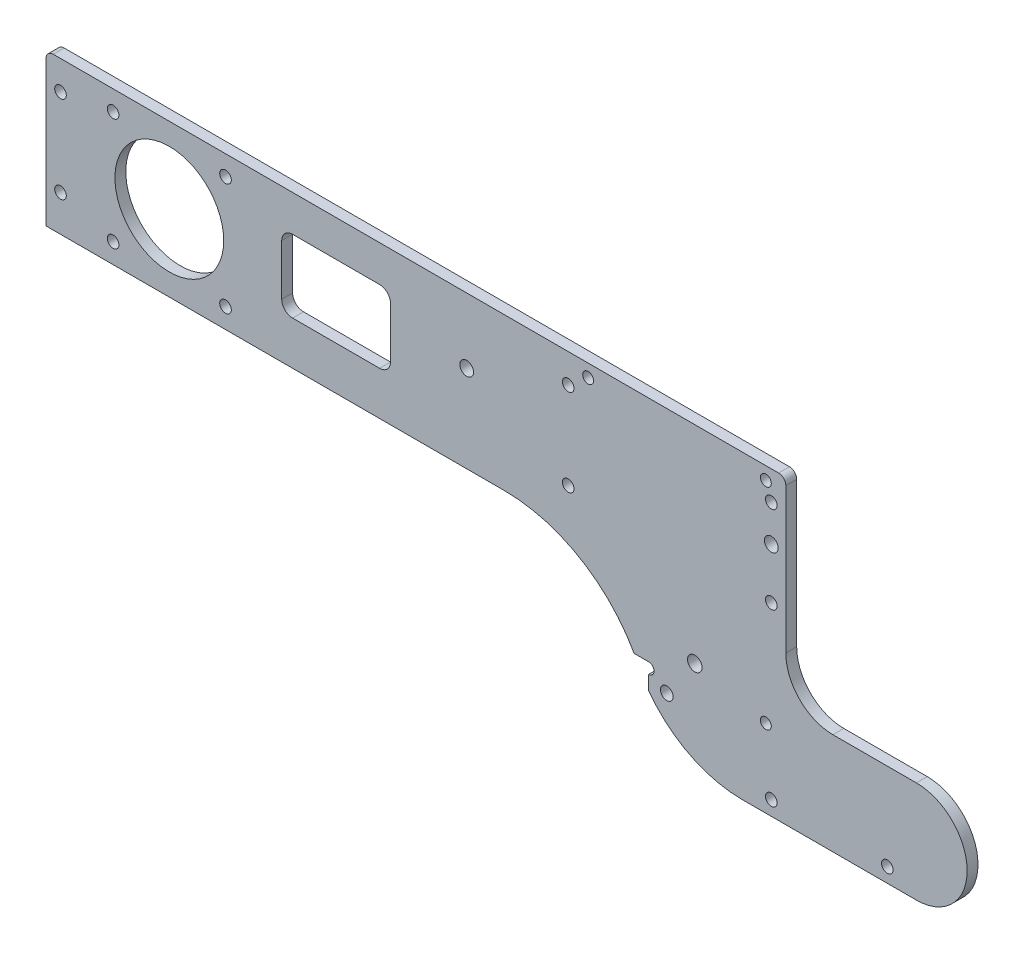
SolidWorks part; units mm, degrees
ref_plane "前视基准面" through (0, 0, 0) normal (0, 0, 1) x (1, 0, 0)
ref_plane "上视基准面" through (0, 0, 0) normal (0, 1, 0) x (1, 0, 0)
ref_plane "右视基准面" through (0, 0, 0) normal (1, 0, 0) x (0, 0, -1)
other "Configuration Table"
sketch "草图1" plane through (0, 0, 0) normal (0, 0, 1) x (1, 0, 0)
  line L1 (-34, 0) -> (-34, 40)
  line L3 (170, 40) -> (170, 0)
  line L4 (-15.5, 5.5) -> (15.5, 5.5) construction
  line L10 (-32, 42) -> (168, 42)
  line L15 (-34, 0) -> (92.3875, 0)
  line L17 (158, -41) -> (206, -41)
  line L20 (166, -37) -> (198, -37) construction
  line L21 (206, -13) -> (183, -13)
  circle A0 centre (15.5, 5.5) radius 1.6
  circle A1 centre (-15.5, 5.5) radius 1.6
  circle A2 centre (-15.5, 36.5) radius 1.6
  circle A3 centre (15.5, 36.5) radius 1.6
  circle A4 centre (166, 34) radius 1.6
  circle A5 centre (166, 10) radius 1.6
  circle A6 centre (-30, 10) radius 1.6
  circle A7 centre (-30, 34) radius 1.6
  arc A8 (168, 42) -> (170, 40) centre (168, 40) cw
  arc A9 (-34, 40) -> (-32, 42) centre (-32, 40) cw
  circle A10 centre (0, 21) radius 15
  arc A11 (92.3875, 0) -> (129.2384, -23.0274) centre (92.3875, -41) cw
  arc A13 (129.2384, -23.0274) -> (158, -41) centre (158, -9) ccw
  arc A14 (206, -41) -> (206, -13) centre (206, -27) ccw
  circle A16 centre (166, -37) radius 1.6
  circle A17 centre (198, -37) radius 1.6
  circle A24 centre (110, 34) radius 1.6
  circle A25 centre (110, 10) radius 1.6
  arc A27 (170, 0) -> (183, -13) centre (183, 0) ccw
  point P8 (0, 5.5)
  point P34 (-34, 42)
  point P48 (182, -41)
  point P49 (182, -37)
  dimension "D3" = 3.2
  dimension "D10" = 3.2
  dimension "D11" = 2
  dimension "D13" = 30
  dimension "D14" = 30
  dimension "D18" = 41
  dimension "D20" = 14
  dimension "D19" = 42
  dimension "D23" = 56
  dimension "D24" = 32
  dimension "D27" = 3.2
  dimension "D21" = 200
  dimension "D2" = 31
  dimension "D4" = 31
  dimension "D5" = 31
  dimension "D6" = 42
  dimension "D7" = 204
  dimension "D8" = 8
  dimension "D9" = 42
  dimension "D12" = 15.5
  dimension "D15" = 34
  dimension "D16" = 4
  dimension "D17" = 10
  dimension "D25" = 48
  dimension "D26" = 32
  dimension "D28" = 4
  dimension "D29" = 21
extrude "凸台-拉伸1" add sketch "草图1" along normal blind 3
sketch "草图3" plane through (0, 0, 3) normal (0, 0, 1) x (1, 0, 0)
  line L0 (158, -41) -> (206, -41) construction
  line L1 (128.1786, -21) -> (132.1786, -21)
  line L2 (128.1786, -21) -> (128.1786, -41)
  line L3 (128.1786, -41) -> (132.1786, -41)
  line L4 (132.1786, -21) -> (132.1786, -41)
  arc A1 (129.2384, -23.0274) -> (92.3875, 0) centre (92.3875, -41) ccw construction
  dimension "D1" = 20
  dimension "D2" = 4
extrude "切除-拉伸2" cut sketch "草图3" against normal blind 10
sketch "草图4" plane through (0, 0, 0) normal (0, 0, -1) x (-1, 0, 0)
  line L0 (-132.1786, -21) -> (-142.1786, -31)
  line L1 (-132.1786, -21) -> (-142.1786, -21)
  line L2 (-132.1786, -21) -> (-132.1786, -31)
  line L3 (-132.1786, -31) -> (-142.1786, -31)
  line L4 (-142.1786, -21) -> (-142.1786, -31)
  dimension "D1" = 10
  dimension "D2" = 10
sketch "草图5" plane through (0, 0, 0) normal (0, 0, -1) x (-1, 0, 0)
  line L0 (-132.1786, -21) -> (-142.1786, -31) construction
  point P0 (-137.1786, -26)
hole_wizard "孔1" positions "草图5" profile "草图6" legacy end condition through all
sketch "草图6" plane through (137.1786, -26, 0) normal (1, 0, 0) x (0, 1, 0)
  line L0 (0, 0) -> (0, 3)
  line L1 (0, 3) -> (1.75, 3)
  line L2 (1.75, 3) -> (1.75, 0)
  line L3 (1.75, 0) -> (0, 0)
  line L4 (0, 110) -> (0, -10) construction
  dimension "直径" = 3.5
  dimension "深度" = 3
sketch "草图10" plane through (0, 0, 0) normal (0, 0, -1) x (-1, 0, 0)
  line L1 (-168, 42) -> (-112, 42)
  line L2 (-168, 42) -> (-168, -43)
  line L3 (-168, -43) -> (-112, -43)
  line L4 (-112, 42) -> (-112, -43)
  line L5 (-164.5, 38.5) -> (-115.5, 38.5)
  line L6 (-164.5, 38.5) -> (-164.5, -19.5)
  line L7 (-164.5, -19.5) -> (-115.5, -19.5)
  line L8 (-115.5, 38.5) -> (-115.5, -19.5)
  dimension "D1" = 85
  dimension "D2" = 56
  dimension "D3" = 3.5
  dimension "D4" = 3.5
  dimension "D5" = 58
  dimension "D6" = 49
sketch "草图11" plane through (0, 0, 0) normal (0, 0, -1) x (-1, 0, 0)
  point P0 (-164.5, 38.5)
  point P3 (-115.5, 38.5)
  point P6 (-164.5, -19.5)
hole_wizard "孔3" positions "草图11" profile "草图12" legacy end condition through all
sketch "草图12" plane through (164.5, 38.5, 0) normal (1, 0, 0) x (0, 1, 0)
  line L0 (0, 0) -> (0, 3)
  line L1 (0, 3) -> (1.5, 3)
  line L2 (1.5, 3) -> (1.5, 0)
  line L3 (1.5, 0) -> (0, 0)
  line L4 (0, 110) -> (0, -10) construction
  dimension "直径" = 3
  dimension "深度" = 3
sketch "草图18" plane through (0, 0, 0) normal (0, 0, -1) x (-1, 0, 0)
  line L0 (-166, 34) -> (-166, 24)
  line L2 (-166, 24) -> (-82, 24)
  dimension "D1" = 10
  dimension "D2" = 84
sketch "草图19" plane through (0, 0, 0) normal (0, 0, -1) x (-1, 0, 0)
  point P0 (-166, 24)
  point P3 (-82, 24)
hole_wizard "孔6" positions "草图19" profile "草图20" legacy
sketch "草图20" plane through (166, 24, 0) normal (1, 0, 0) x (0, 1, 0)
  line L0 (0, 0) -> (0, 3)
  line L1 (0, 3) -> (1.9, 3)
  line L2 (1.9, 3) -> (1.9, 0)
  line L3 (1.9, 0) -> (0, 0)
  line L4 (0, 110) -> (0, -10) construction
  dimension "直径" = 3.8
  dimension "深度" = 3
sketch "草图23" plane through (0, 0, 0) normal (0, 0, -1) x (-1, 0, 0)
  point P0 (-144.906, -15.042)
hole_wizard "孔8" positions "草图23" profile "草图24" legacy
sketch "草图24" plane through (144.906, -15.042, 0) normal (1, 0, 0) x (0, 1, 0)
  line L0 (0, 0) -> (0, 3)
  line L1 (0, 3) -> (2, 3)
  line L2 (2, 3) -> (2, 0)
  line L3 (2, 0) -> (0, 0)
  line L4 (0, 110) -> (0, -10) construction
  dimension "直径" = 4
  dimension "深度" = 3
sketch "草图25" plane through (0, 0, 0) normal (0, 0, -1) x (-1, 0, 0)
  line L0 (-168, 42) -> (32, 42) construction
  line L1 (-31, 32) -> (-61, 32)
  line L2 (-31, 32) -> (-31, 12)
  line L3 (-31, 12) -> (-61, 12)
  line L4 (-61, 32) -> (-61, 12)
  line L5 (-31, 32) -> (-61, 12) construction
  line L6 (-31, 12) -> (-61, 32) construction
  line L7 (34, 40) -> (34, 0) construction
  point P0 (-46, 22)
  dimension "D1" = 20
  dimension "D2" = 80
  dimension "D3" = 30
  dimension "D4" = 20
extrude "切除-拉伸3" cut sketch "草图25" against normal blind 10
fillet "圆角1" radius 3 4 edges at (61, 12, 1.5) (31, 12, 1.5) (31, 32, 1.5) (61, 32, 1.5)
sketch "草图26" plane through (0, 0, 0) normal (0, 0, -1) x (-1, 0, 0)
  line L0 (-132.1786, -21) -> (-132.1786, -31) construction
  point P0 (-132.1786, -22.5)
  dimension "D1" = 1.5
hole_wizard "孔9" positions "草图26" profile "草图27" legacy end condition up to next
sketch "草图27" plane through (132.1786, -22.5, 0) normal (1, 0, 0) x (0, 1, 0)
  line L0 (0, 0) -> (0, 3)
  line L1 (0, 3) -> (1.5, 3)
  line L2 (1.5, 3) -> (1.5, 0)
  line L3 (1.5, 0) -> (0, 0)
  line L4 (0, 110) -> (0, -10) construction
  dimension "直径" = 3
  dimension "深度" = 3
